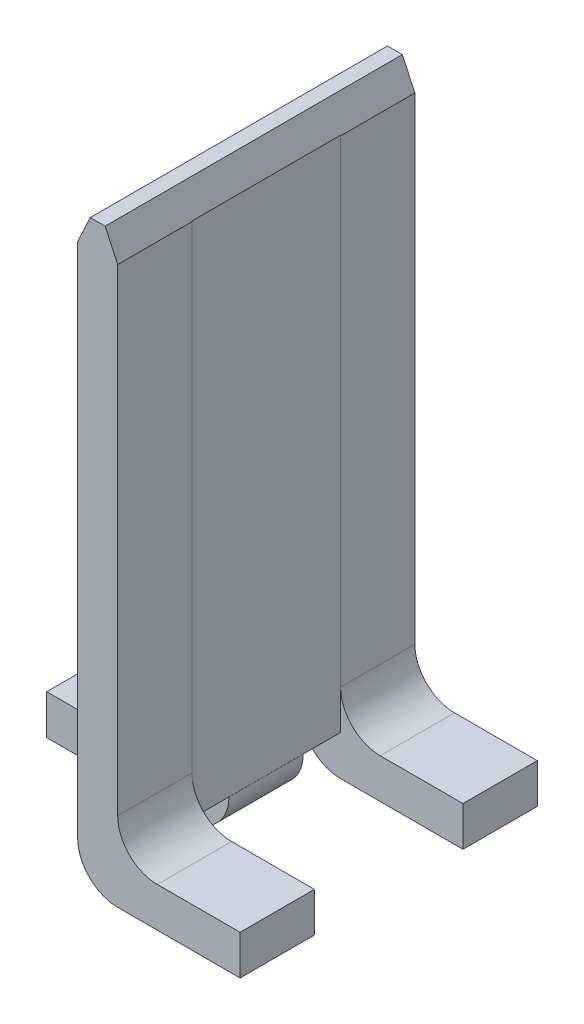
SolidWorks part; units mm, degrees
ref_plane "Front Plane" through (0, 0, 0) normal (0, 0, 1) x (1, 0, 0)
ref_plane "Top Plane" through (0, 0, 0) normal (0, 1, 0) x (1, 0, 0)
ref_plane "Right Plane" through (0, 0, 0) normal (1, 0, 0) x (0, 0, -1)
sketch "Sketch1" plane through (0, 0, 0) normal (0, 0, 1) x (1, 0, 0)
  line L0 (0.4104, 5.4322) -> (0.1524, 5.9855)
  line L2 (-0.4104, -5.1692) -> (-0.4104, 5.4322)
  line L3 (-0.1524, 5.9855) -> (0.1524, 5.9855)
  line L5 (-0.4064, -5.9855) -> (0.4064, 5.9855) construction
  line L6 (-0.4064, 5.9855) -> (0.4064, -5.9855) construction
  line L7 (0, 5.9855) -> (0, -5.9855) construction
  line L9 (-0.4104, 5.4322) -> (-0.1524, 5.9855)
  line L10 (0.4104, -5.1647) -> (0.4104, 5.4322) construction
  line L11 (0.4064, -5.9855) -> (2.921, -5.9855)
  line L13 (1.2232, -5.1727) -> (2.921, -5.1727)
  line L14 (2.921, -5.9855) -> (2.921, -5.1727)
  line L15 (0.4104, -4.3599) -> (0.4104, 5.4322)
  arc A0 (-0.4104, -5.1692) -> (0.4064, -5.9855) centre (0.4104, -5.1647) ccw
  arc A2 (0.4104, -4.3599) -> (1.2232, -5.1727) centre (1.2232, -4.3599) ccw
  point P0 (0, 0)
  point P15 (1.3156, -4.2101)
  point P16 (0.4104, -4.3599)
  point P18 (1.2232, -5.1727)
  dimension "D1" = 1.6256
  dimension "D3" = 0.254
  dimension "D5" = 0.8128
  dimension "D6" = 2.921
extrude "Boss-Extrude1" add sketch "Sketch1" along normal blind 6.096
sketch "Sketch2" plane through (-0.4104, 0, 0) normal (-1, 0, 0) x (0, 0, 1)
  line L0 (3.048, -5.9855) -> (3.048, -5.1692) construction
  line L1 (0, -5.1692) -> (6.096, -5.1692) construction
  line L2 (0, -5.1692) -> (0, -5.9855) construction
  line L3 (0, -5.9855) -> (6.096, -5.9855) construction
  line L4 (6.096, -5.1692) -> (6.096, -5.9855) construction
  line L10 (1.524, -5.1692) -> (4.572, -5.1692)
  line L11 (1.524, -5.1692) -> (1.524, -5.9855)
  line L12 (6.096, -5.9855) -> (4.572, -5.9855) construction
  line L13 (6.096, -5.9855) -> (6.096, -5.1692) construction
  line L14 (6.096, -5.1692) -> (4.572, -5.1692) construction
  line L15 (4.572, -5.9855) -> (4.572, -5.1692) construction
  line L16 (1.524, -5.9855) -> (0, -5.9855) construction
  line L17 (1.524, -5.9855) -> (1.524, -5.1692) construction
  line L18 (1.524, -5.1692) -> (0, -5.1692) construction
  line L19 (0, -5.9855) -> (0, -5.1692) construction
  line L20 (1.524, -5.9855) -> (4.572, -5.9855)
  line L21 (4.572, -5.1692) -> (4.572, -5.9855)
  point P8 (3.048, -5.5774)
  dimension "D2" = 1.524
  dimension "D3" = 1.524
extrude "Cut-Extrude1" cut sketch "Sketch2" against normal through all
sketch "Sketch3" plane through (-0.4104, 0, 0) normal (-1, 0, 0) x (0, 0, 1)
  line L0 (3.048, -5.9855) -> (3.048, -5.1692) construction
  line L1 (4.572, -5.9855) -> (1.524, -5.9855) construction
  line L2 (4.572, -5.9855) -> (4.572, -5.1692) construction
  line L3 (4.572, -5.1692) -> (1.524, -5.1692) construction
  line L4 (1.524, -5.9855) -> (1.524, -5.1692) construction
  line L6 (2.286, -5.9855) -> (3.81, -5.9855)
  line L7 (2.286, -5.9855) -> (2.286, -5.1692)
  line L8 (2.286, -5.1692) -> (3.81, -5.1692)
  line L9 (3.81, -5.9855) -> (3.81, -5.1692)
  line L10 (2.286, -5.9855) -> (3.81, -5.1692) construction
  line L11 (2.286, -5.1692) -> (3.81, -5.9855) construction
  point P8 (3.048, -5.5774)
  dimension "D1" = 1.524
extrude "Boss-Extrude2" add sketch "Sketch3" along normal blind 2.921 separate body
sketch "Sketch4" plane through (0, 0, 3.81) normal (0, 0, 1) x (1, 0, 0)
  line L0 (-0.4104, -5.1692) -> (1.2232, -5.1727) construction
  line L1 (-0.4104, -5.1692) -> (-0.4104, -5.9855) construction
  line L6 (-0.4104, 5.4322) -> (-0.4104, -5.1692) construction
  line L12 (-3.3314, -5.1692) -> (-0.4104, -5.1692) construction
  line L13 (-1.2232, -4.3564) -> (0.4104, -4.3599) construction
  line L14 (-1.2232, -4.3564) -> (-1.2232, -5.1692) construction
  line L15 (-1.2232, -5.1692) -> (-1.2232, -5.9855)
  line L16 (-3.3314, -5.9855) -> (-0.4104, -5.9855) construction
  line L17 (-1.2232, -5.9855) -> (-0.4104, -5.9855)
  line L18 (0.4059, -5.1709) -> (-0.4104, -5.1692)
  line L19 (-0.4104, -5.1692) -> (-0.4104, -4.3581)
  arc A6 (-0.4104, -5.9855) -> (0.4059, -5.1709) centre (-0.4104, -5.1692) ccw
  arc A7 (-1.2232, -5.1692) -> (-0.4104, -4.3581) centre (-1.2232, -4.3564) ccw
  dimension "D1" = 1.6256
extrude "Boss-Extrude3" add sketch "Sketch4" against normal blind 1.524
sketch "Sketch7" plane through (0, -5.1692, 0) normal (0, -1, 0) x (1, 0, 0)
  line L1 (0.4064, 4.572) -> (1.1482, 4.572)
  line L2 (0.4064, 4.572) -> (0.4064, 1.524)
  line L3 (0.4064, 1.524) -> (1.1482, 1.524)
  line L4 (1.1482, 4.572) -> (1.1482, 1.524)
extrude "Cut-Extrude3" cut sketch "Sketch7" against normal through all
